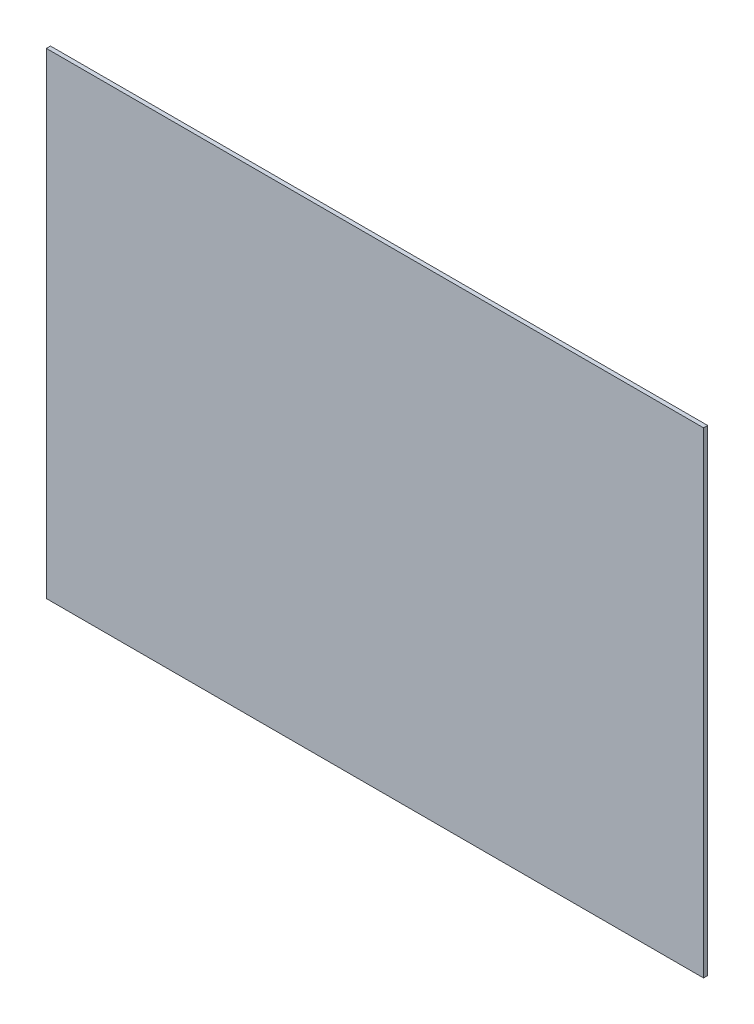
SolidWorks part; units mm, degrees
ref_plane "Plan de face" through (0, 0, 0) normal (0, 0, 1) x (1, 0, 0)
ref_plane "Plan de dessus" through (0, 0, 0) normal (0, 1, 0) x (1, 0, 0)
ref_plane "Plan de droite" through (0, 0, 0) normal (1, 0, 0) x (0, 0, -1)
sketch "Esquisse1" plane through (0, 0, 0) normal (0, 0, 1) x (1, 0, 0)
  line L1 (-400, 290) -> (400, 290)
  line L2 (-400, 290) -> (-400, -290)
  line L3 (-400, -290) -> (400, -290)
  line L4 (400, 290) -> (400, -290)
  line L5 (-400, 290) -> (400, -290) construction
  line L6 (-400, -290) -> (400, 290) construction
  point P0 (0, 0)
  dimension "D1" = 800
  dimension "580" = 580
extrude "Boss.-Extru.1" add sketch "Esquisse1" along normal blind 5
